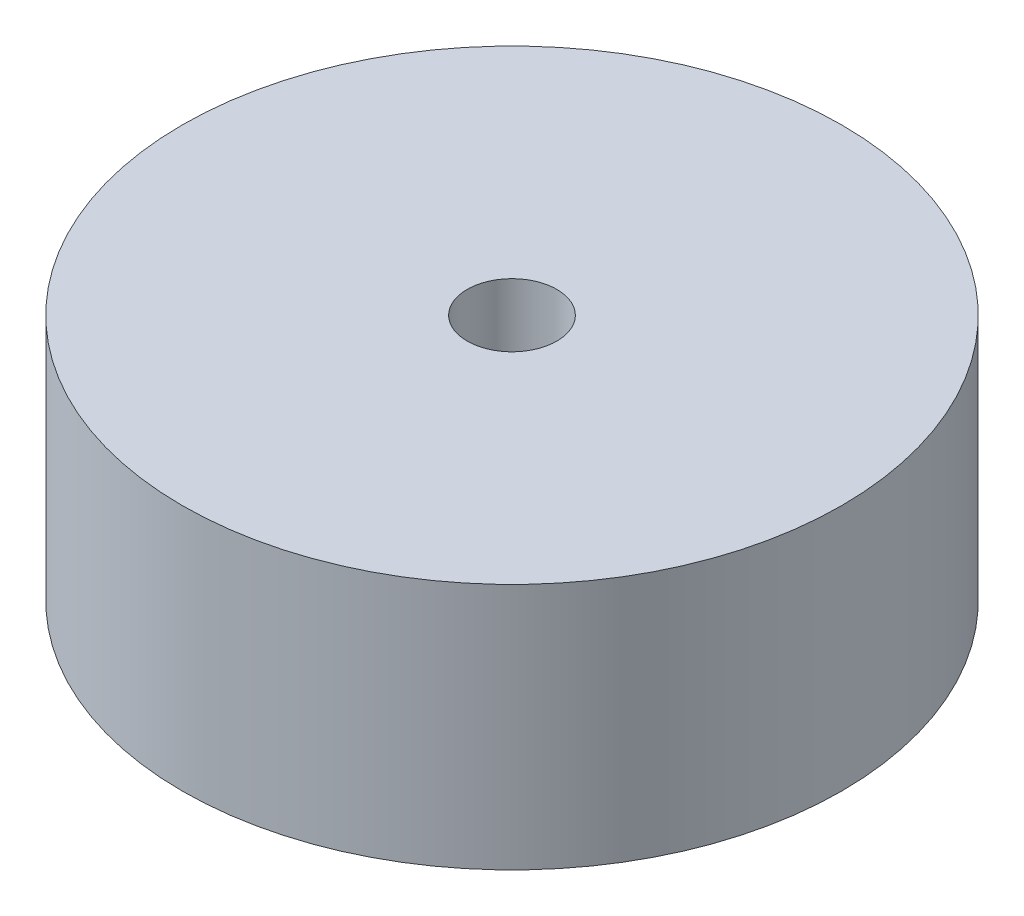
SolidWorks part; units mm, degrees
ref_plane "Front Plane" through (0, 0, 0) normal (0, 0, 1) x (1, 0, 0)
ref_plane "Top Plane" through (0, 0, 0) normal (0, 1, 0) x (1, 0, 0)
ref_plane "Right Plane" through (0, 0, 0) normal (1, 0, 0) x (0, 0, -1)
sketch "Sketch1" plane through (0, 0, 0) normal (0, 1, 0) x (1, 0, 0)
  circle A0 centre (0, 0) radius 25.4
  dimension "D1" = 50.8
extrude "Boss-Extrude1" add sketch "Sketch1" along normal blind 19.05
hole_wizard "5/16-24 Tapped Hole1" positions "Sketch3" profile "Sketch2" tap size "5/16-24" standard "ANSI Inch" end condition up to next
sketch "Sketch3" plane through (0, 19.05, 0) normal (0, 1, 0) x (1, 0, 0)
  point P0 (0, 0)
sketch "Sketch2" plane through (0, 19.05, 0) normal (1, 0, 0) x (0, 0, 1)
  line L0 (0, 0) -> (0, 19.05)
  line L1 (0, 19.05) -> (3.4544, 19.05)
  line L2 (3.4544, 19.05) -> (3.4544, 0)
  line L5 (3.4544, 0) -> (0, 0)
  line L11 (0, -6.35) -> (0, 107.95) construction
  dimension "Thru Tap Drill Dia." = 6.9088
  dimension "Thru Tap Drill Depth" = 19.05
cosmetic thread "Hole Thread1" parameters "D2"=7.9375
